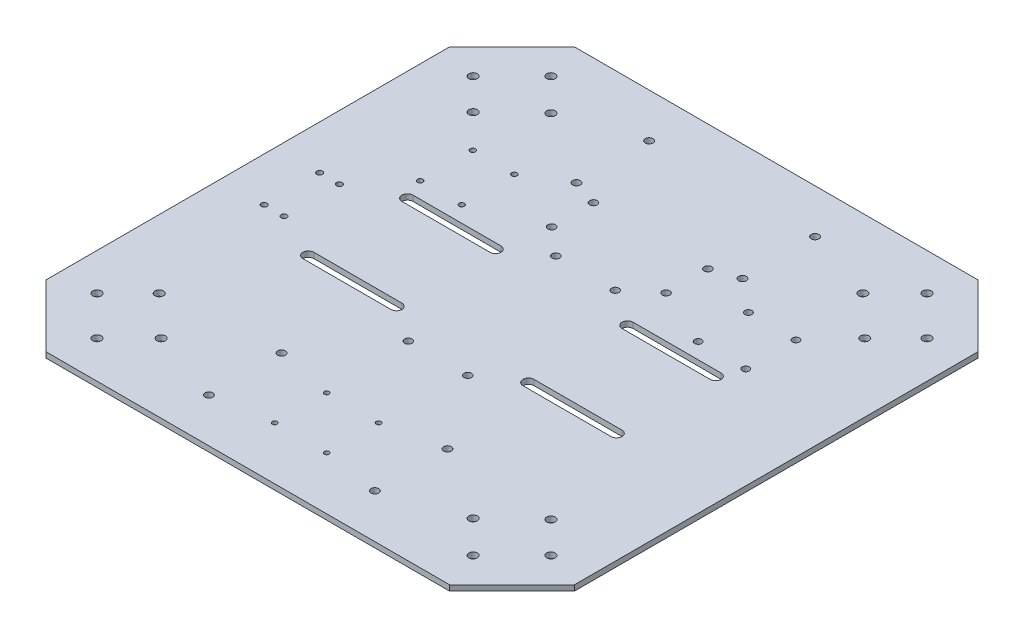
SolidWorks part; units mm, degrees
ref_plane "Front Plane" through (0, 0, 0) normal (0, 0, 1) x (1, 0, 0)
ref_plane "Top Plane" through (0, 0, 0) normal (0, 1, 0) x (1, 0, 0)
ref_plane "Right Plane" through (0, 0, 0) normal (1, 0, 0) x (0, 0, -1)
sketch "Sketch1" plane through (0, 0, 0) normal (0, 1, 0) x (1, 0, 0)
  line L0 (-61.766, 15.7353) -> (-25.845, 51.6564)
  line L1 (-61.766, 51.6564) -> (243.034, 51.6564)
  line L2 (-61.766, 51.6564) -> (-61.766, -253.1436)
  line L3 (-61.766, -253.1436) -> (243.034, -253.1436)
  line L4 (243.034, 51.6564) -> (243.034, -253.1436)
  line L5 (90.634, 95.069) -> (90.634, -294.9418) construction
  line L6 (-86.5248, -100.7436) -> (277.558, -100.7436) construction
  line L7 (243.034, 15.7353) -> (207.1129, 51.6564)
  line L8 (243.034, -217.2226) -> (207.1129, -253.1436)
  line L9 (-61.766, -217.2226) -> (-25.845, -253.1436)
  line L10 (128.734, -72.1686) -> (179.534, -72.1686) construction
  line L11 (128.734, -68.9936) -> (179.534, -68.9936)
  line L12 (128.734, -75.3436) -> (179.534, -75.3436)
  line L13 (128.734, -129.3186) -> (179.534, -129.3186) construction
  line L14 (128.734, -132.4936) -> (179.534, -132.4936)
  line L15 (128.734, -126.1436) -> (179.534, -126.1436)
  line L16 (52.534, -129.3186) -> (1.734, -129.3186) construction
  line L17 (52.534, -132.4936) -> (1.734, -132.4936)
  line L18 (52.534, -126.1436) -> (1.734, -126.1436)
  line L19 (52.534, -72.1686) -> (1.734, -72.1686) construction
  line L20 (52.534, -68.9936) -> (1.734, -68.9936)
  line L21 (52.534, -75.3436) -> (1.734, -75.3436)
  arc A0 (128.734, -68.9936) -> (128.734, -75.3436) centre (128.734, -72.1686) ccw
  arc A1 (179.534, -75.3436) -> (179.534, -68.9936) centre (179.534, -72.1686) ccw
  arc A2 (128.734, -132.4936) -> (128.734, -126.1436) centre (128.734, -129.3186) cw
  arc A3 (179.534, -126.1436) -> (179.534, -132.4936) centre (179.534, -129.3186) cw
  arc A4 (52.534, -132.4936) -> (52.534, -126.1436) centre (52.534, -129.3186) ccw
  arc A5 (1.734, -126.1436) -> (1.734, -132.4936) centre (1.734, -129.3186) ccw
  arc A6 (52.534, -68.9936) -> (52.534, -75.3436) centre (52.534, -72.1686) cw
  arc A7 (1.734, -75.3436) -> (1.734, -68.9936) centre (1.734, -72.1686) cw
  point P8 (90.634, 51.6564)
  point P11 (-61.766, -100.7436)
  point P18 (154.134, -72.1686)
  point P27 (154.134, -129.3186)
  point P34 (27.134, -129.3186)
  point P41 (27.134, -72.1686)
  dimension "D6" = 6.35
  dimension "D1" = 304.8
  dimension "D2" = 304.8
  dimension "D3" = 45
  dimension "D4" = 50.8
  dimension "D5" = 50.8
  dimension "D7" = 38.1
  dimension "D8" = 50.8
extrude "Boss-Extrude1" add sketch "Sketch1" along normal blind 3.175 contours L2 L9 L3 L8 L4 L7 L1 L0 A5 L18 A4 L17 A1 L12 A0 L11 L15 A3 L14 A2 L21 A7 L20 A6
sketch "Sketch2" plane through (0, 3.175, 0) normal (0, 1, 0) x (1, 0, 0)
  line L0 (-40.323, 7.7627) -> (-22.3625, -10.1978) construction
  line L1 (-17.8724, 30.2133) -> (0.6409, 11.7001) construction
  line L2 (-43.8055, 33.6958) -> (20.8232, -30.9329) construction
  line L3 (-61.766, 15.7353) -> (-25.845, 51.6564) construction
  line L7 (90.634, 51.6564) -> (90.634, -253.1436) construction
  line L8 (-25.845, 51.6564) -> (207.1129, 51.6564) construction
  line L9 (-25.845, -253.1436) -> (207.1129, -253.1436) construction
  line L10 (-61.766, -100.7436) -> (243.034, -100.7436) construction
  line L11 (-61.766, 15.7353) -> (-61.766, -217.2226) construction
  line L12 (243.034, 15.7353) -> (243.034, -217.2226) construction
  circle A0 centre (-17.8724, 30.2133) radius 2.4638
  circle A1 centre (0.6409, 11.7001) radius 2.4638
  circle A2 centre (-22.3625, -10.1978) radius 2.4638
  circle A3 centre (-40.323, 7.7627) radius 2.4638
  circle A4 centre (203.6304, -10.1978) radius 2.4638
  circle A5 centre (221.5909, 7.7627) radius 2.4638
  circle A6 centre (180.627, 11.7001) radius 2.4638
  circle A7 centre (199.1403, 30.2133) radius 2.4638
  circle A8 centre (-22.3625, -191.2895) radius 2.4638
  circle A9 centre (-40.323, -209.25) radius 2.4638
  circle A10 centre (-17.8724, -231.7006) radius 2.4638
  circle A11 centre (0.6409, -213.1873) radius 2.4638
  circle A12 centre (221.5909, -209.25) radius 2.4638
  circle A13 centre (199.1403, -231.7006) radius 2.4638
  circle A14 centre (180.627, -213.1873) radius 2.4638
  circle A15 centre (203.6304, -191.2895) radius 2.4638
  dimension "D3" = 4.9276
  dimension "D4" = 4.9276
  dimension "D5" = 4.9276
  dimension "D6" = 4.9276
  dimension "D1" = 25.4
  dimension "D2" = 31.75
  dimension "D7" = 15.875
extrude "Cut-Extrude1" cut sketch "Sketch2" against normal blind 6.35
sketch "Sketch3" plane through (0, 3.175, 0) normal (0, 1, 0) x (1, 0, 0)
  line L0 (-61.766, -100.7436) -> (278.5513, -100.7436) construction
  line L2 (-61.766, 15.7353) -> (-61.766, -217.2226) construction
  line L3 (90.634, 51.6564) -> (90.634, -273.1997) construction
  line L4 (-25.845, 51.6564) -> (207.1129, 51.6564) construction
  circle A0 centre (73.362, -58.1986) radius 2.159
  circle A1 centre (107.652, -58.1986) radius 2.159
  circle A2 centre (73.362, -143.2886) radius 2.159
  circle A3 centre (107.652, -143.2886) radius 2.159
  point P10 (-61.766, -100.7436)
  dimension "D3" = 4.318
  dimension "D4" = 4.318
  dimension "D5" = 4.318
  dimension "D6" = 4.318
  dimension "D1" = 34.29
  dimension "D2" = 85.09
  dimension "D7" = 42.545
  dimension "D8" = 17.272
extrude "Cut-Extrude2" cut sketch "Sketch3" against normal blind 6.35
sketch "Sketch4" plane through (0, 3.175, 0) normal (0, 1, 0) x (1, 0, 0)
  line L0 (90.634, 51.6564) -> (90.634, -36.4614) construction
  line L1 (-25.845, 51.6564) -> (207.1129, 51.6564) construction
  line L2 (-61.766, -100.7436) -> (257.447, -100.7436) construction
  line L3 (-61.766, 15.7353) -> (-61.766, -217.2226) construction
  circle A0 centre (42.755, 26.2564) radius 2.2225
  circle A1 centre (138.513, 26.2564) radius 2.2225
  circle A2 centre (42.755, -15.6536) radius 2.2225
  circle A3 centre (138.513, -15.6536) radius 2.2225
  circle A4 centre (138.513, -185.8336) radius 2.2225
  circle A5 centre (42.755, -185.8336) radius 2.2225
  circle A6 centre (138.513, -227.7436) radius 2.2225
  circle A7 centre (42.755, -227.7436) radius 2.2225
  dimension "D1" = 4.445
  dimension "D2" = 4.445
  dimension "D3" = 4.445
  dimension "D4" = 4.445
  dimension "D5" = 95.758
  dimension "D6" = 41.91
  dimension "D7" = 47.879
  dimension "D8" = 25.4
extrude "Cut-Extrude3" cut sketch "Sketch4" against normal through all
sketch "Sketch5" plane through (0, 3.175, 0) normal (0, 1, 0) x (1, 0, 0)
  line L0 (-61.766, -100.7436) -> (105.2484, -100.7436) construction
  line L1 (-61.766, 15.7353) -> (-61.766, -217.2226) construction
  circle A0 centre (-36.366, -84.7416) radius 1.651
  circle A1 centre (-24.936, -84.7416) radius 1.651
  circle A2 centre (-24.936, -116.7456) radius 1.651
  circle A3 centre (-36.366, -116.7456) radius 1.651
  dimension "D1" = 3.302
  dimension "D2" = 3.302
  dimension "D3" = 11.43
  dimension "D4" = 16.002
  dimension "D5" = 25.4
extrude "Cut-Extrude4" cut sketch "Sketch5" against normal through all
sketch "Sketch6" plane through (0, 3.175, 0) normal (0, 1, 0) x (1, 0, 0)
  line L0 (243.034, 15.7353) -> (243.034, -217.2226) construction
  line L1 (-25.845, 51.6564) -> (207.1129, 51.6564) construction
  line L2 (90.634, 51.6564) -> (90.634, -253.1436) construction
  line L3 (-25.845, -253.1436) -> (207.1129, -253.1436) construction
  line L4 (-61.766, 15.7353) -> (-61.766, -217.2226) construction
  circle A0 centre (157.182, -30.8936) radius 2.032
  circle A1 centre (157.182, -59.8496) radius 2.032
  circle A2 centre (184.614, -59.8496) radius 2.032
  circle A3 centre (184.614, -30.8936) radius 2.032
  circle A4 centre (57.614, -20.7336) radius 2.159
  circle A5 centre (57.614, -44.8636) radius 2.159
  circle A6 centre (123.654, -44.8636) radius 2.159
  circle A7 centre (123.654, -20.7336) radius 2.159
  circle A8 centre (75.648, -192.6916) radius 1.397
  circle A9 centre (75.648, -222.6636) radius 1.397
  circle A10 centre (105.62, -222.6636) radius 1.397
  circle A11 centre (105.62, -192.6916) radius 1.397
  circle A12 centre (-3.389, -29.3696) radius 1.55
  circle A13 centre (-3.346, -59.7696) radius 1.55
  circle A14 centre (20.6111, -29.3696) radius 1.55
  circle A15 centre (20.6111, -59.7696) radius 1.55
  point P40 (0, 0)
  point P41 (0, 0)
  point P42 (0, 0)
  dimension "D1" = 4.064
  dimension "D6" = 4.318
  dimension "D7" = 4.318
  dimension "D10" = 2.794
  dimension "D11" = 2.794
  dimension "D15" = 3.1
  dimension "D16" = 3.1
  dimension "D18" = 3.1
  dimension "D19" = 3.1
  dimension "D2" = 27.432
  dimension "D3" = 28.956
  dimension "D4" = 58.42
  dimension "D5" = 82.55
  dimension "D8" = 33.02
  dimension "D9" = 24.13
  dimension "D12" = 14.986
  dimension "D13" = 29.972
  dimension "D14" = 30.48
  dimension "D17" = 30.4
  dimension "D20" = 24
  dimension "D21" = 72.39
  dimension "D22" = 58.42
  dimension "D23" = 81.026
extrude "Cut-Extrude5" cut sketch "Sketch6" against normal through all
